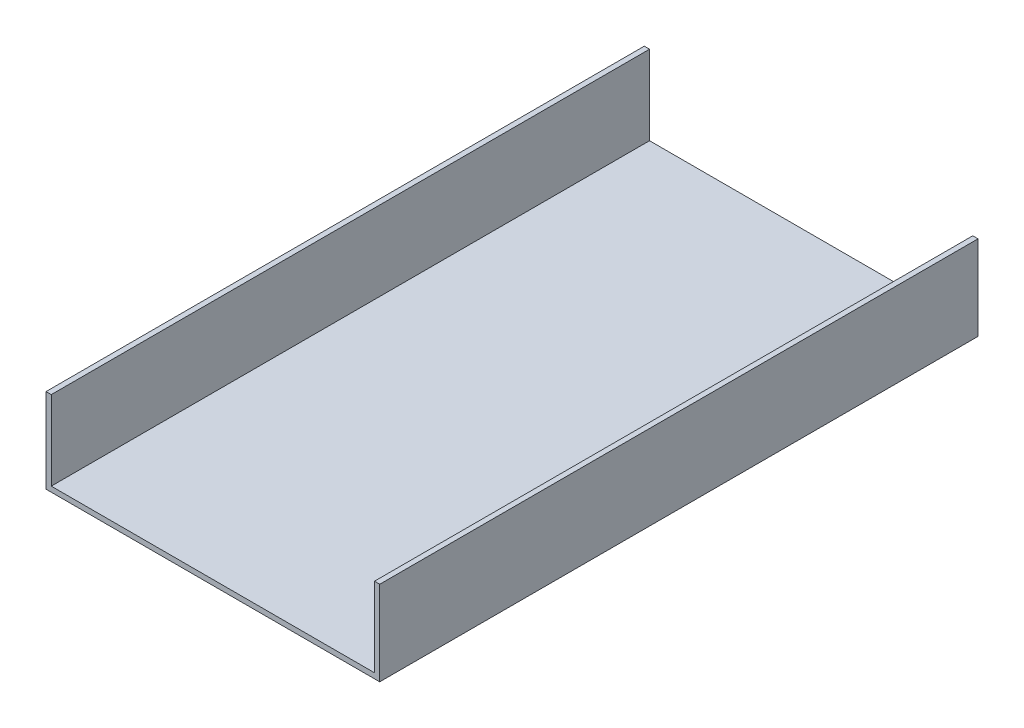
SolidWorks part; units mm, degrees
ref_plane "Alzado" through (0, 0, 0) normal (0, 0, 1) x (1, 0, 0)
ref_plane "Planta" through (0, 0, 0) normal (0, 1, 0) x (1, 0, 0)
ref_plane "Vista lateral" through (0, 0, 0) normal (1, 0, 0) x (0, 0, -1)
sketch "Croquis1" plane through (0, 0, 0) normal (0, 0, 1) x (1, 0, 0)
  line L1 (-77.9171, 12.6133) -> (23.6229, 12.6133)
  line L2 (-77.9171, 12.6133) -> (-77.9171, -13.1067)
  line L3 (-77.9171, -13.1067) -> (23.6229, -13.1067)
  line L4 (23.6229, 12.6133) -> (23.6229, -13.1067)
  line L5 (-76.3171, 11.0133) -> (22.0229, 11.0133)
  line L6 (-76.3171, 11.0133) -> (-76.3171, -11.5067)
  line L7 (-76.3171, -11.5067) -> (22.0229, -11.5067)
  line L8 (22.0229, 11.0133) -> (22.0229, -11.5067)
  dimension "D1" = 25.72
  dimension "D2" = 101.54
  dimension "D3" = 1.6
  dimension "D4" = 1.6
  dimension "D5" = 1.6
  dimension "D6" = 1.6
extrude "Saliente-Extruir1" add sketch "Croquis1" along normal mid plane 182.04
sketch "Croquis2" plane through (0, 12.6133, 0) normal (0, 1, 0) x (1, 0, 0)
  line L0 (23.6229, 91.02) -> (-77.9171, 91.02) construction
  line L1 (-76.3171, 91.02) -> (22.0229, 91.02)
  line L2 (-76.3171, 91.02) -> (-76.3171, -91.02)
  line L3 (-76.3171, -91.02) -> (22.0229, -91.02)
  line L4 (22.0229, 91.02) -> (22.0229, -91.02)
  line L5 (23.6229, -91.02) -> (-77.9171, -91.02) construction
  line L6 (-77.9171, -91.02) -> (-77.9171, 91.02) construction
  line L7 (23.6229, -91.02) -> (23.6229, 91.02) construction
  dimension "D1" = 1.6
  dimension "D2" = 1.6
extrude "Cortar-Extruir1" cut sketch "Croquis2" against normal blind 6.04
